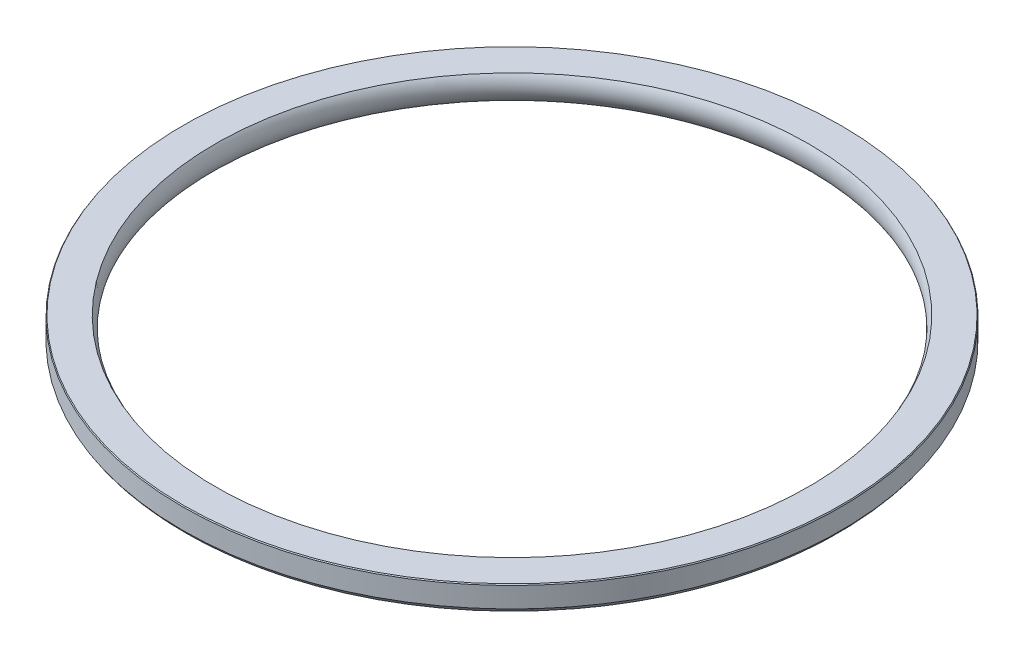
SolidWorks part; units mm, degrees
material "NBR"
ref_plane "Piano frontale" through (0, 0, 0) normal (0, 0, 1) x (1, 0, 0)
ref_plane "Piano superiore" through (0, 0, 0) normal (0, 1, 0) x (1, 0, 0)
ref_plane "Piano destro" through (0, 0, 0) normal (1, 0, 0) x (0, 0, -1)
sketch "Schizzo1" plane through (0, 0, 0) normal (0, 0, 1) x (1, 0, 0)
  line L0 (-14.24, 0) -> (0, 0) construction
  line L1 (0, 0) -> (0, 8.8166) construction
  line L2 (-15, 0.51) -> (-13.5106, 0.51)
  line L3 (-15, -0.4631) -> (-15, 0.4631)
  circle A0 centre (-14.24, 0) radius 0.89
  dimension "D1" = 1.78
  dimension "D2" = 28.48
  dimension "D3" = 30
  dimension "D4" = 0.51
revolve "Rivoluzione1" add sketch "Schizzo1" angle 360 about L1
